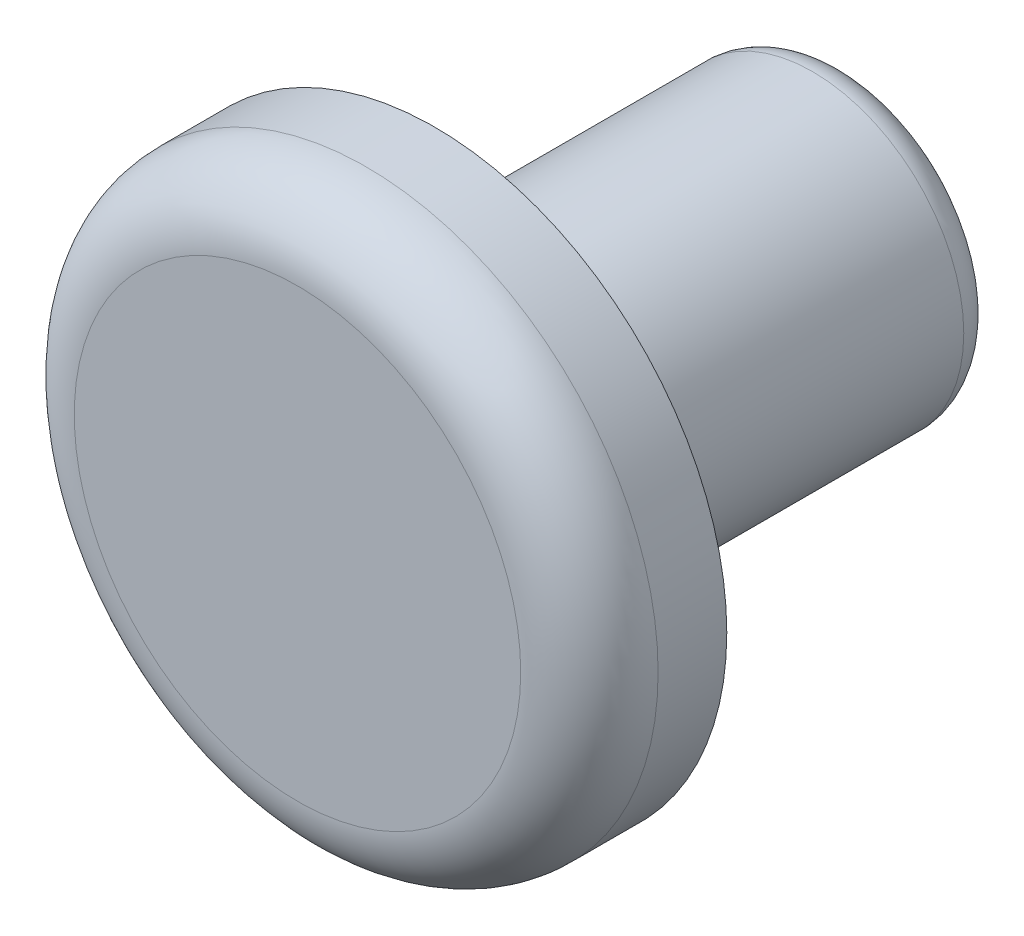
SolidWorks part; units mm, degrees
ref_plane "Plan de face" through (0, 0, 0) normal (0, 0, 1) x (1, 0, 0)
ref_plane "Plan de dessus" through (0, 0, 0) normal (0, 1, 0) x (1, 0, 0)
ref_plane "Plan de droite" through (0, 0, 0) normal (1, 0, 0) x (0, 0, -1)
sketch "Esquisse1" plane through (0, 0, 0) normal (0, 0, 1) x (1, 0, 0)
  circle A0 centre (0, 0) radius 2.125
  dimension "D1" = 4.25
extrude "Boss.-Extru.1" add sketch "Esquisse1" along normal blind 1
sketch "Esquisse2" plane through (0, 0, 0) normal (0, 0, -1) x (-1, 0, 0)
  circle A0 centre (0, 0) radius 1.1
  dimension "D1" = 2.2
extrude "Boss.-Extru.2" add sketch "Esquisse2" along normal blind 3
fillet "Congé2" radius 0.5 1 edges at (2.125, 0, 1)
fillet "Congé3" radius 0.25 1 edges at (-1.1, 0, -3)
